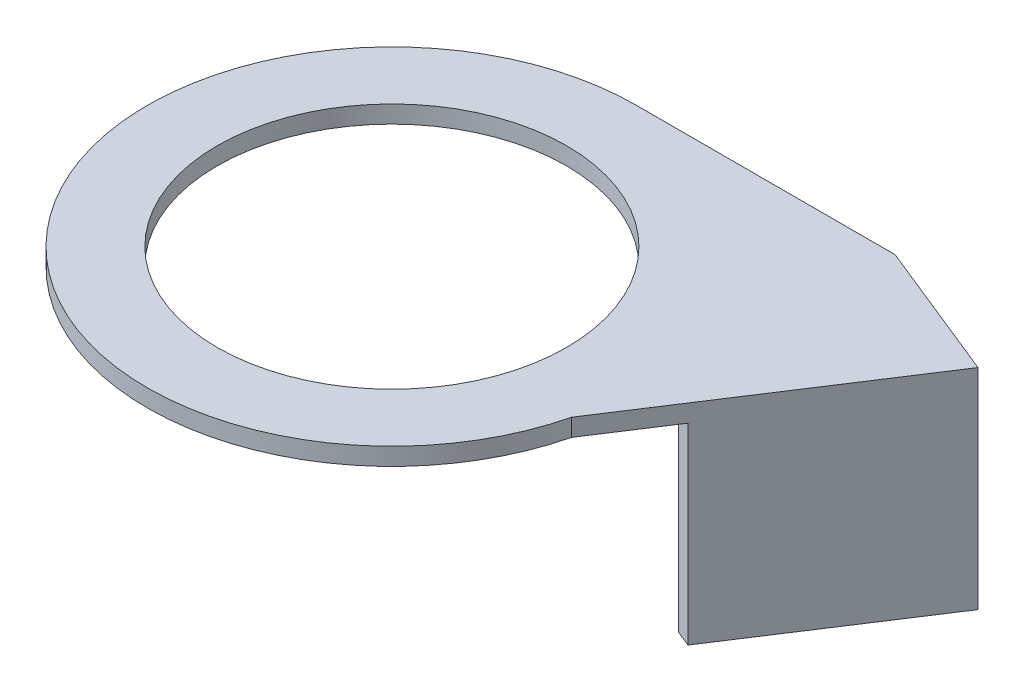
SolidWorks part; units mm, degrees
material "ABS"
ref_plane "Front" through (0, 0, 0) normal (0, 0, 1) x (1, 0, 0)
ref_plane "Top" through (0, 0, 0) normal (0, 1, 0) x (1, 0, 0)
ref_plane "Right" through (0, 0, 0) normal (1, 0, 0) x (0, 0, -1)
sketch "Sketch1" plane through (0, 0, 0) normal (0, 1, 0) x (1, 0, 0)
  line L0 (0, 14) -> (14.8054, 14)
  line L1 (14.8054, 14) -> (22.7702, 10.7781)
  line L2 (22.7702, 10.7781) -> (13.6017, -3.3156)
  circle A0 centre (0, 0) radius 14
  dimension "D1" = 0
extrude "Boss-Extrude1" add sketch "Sketch1" along normal blind 1 contours A0 | A0 L2 L1 L0
sketch "Sketch2" plane through (0, 0, 0) normal (0, -1, 0) x (-1, 0, 0)
  line L0 (-22.7702, 10.7781) -> (-21.8432, 11.1531)
  line L1 (-14.8054, 14) -> (-22.7702, 10.7781) construction
  line L2 (-21.8432, 11.1531) -> (-15.2995, 1.0942)
  line L3 (-22.7702, 10.7781) -> (-13.6017, -3.3156) construction
  line L4 (-22.7702, 10.7781) -> (-16.2265, 0.7192)
  line L5 (-16.2265, 0.7192) -> (-15.2995, 1.0942)
  dimension "D1" = 12
extrude "Boss-Extrude2" add sketch "Sketch2" along normal blind 11
sketch "Sketch3" plane through (0, 0, 0) normal (0, -1, 0) x (-1, 0, 0)
  line L0 (-18.0654, 12.6812) -> (-14.3982, 7.044)
  line L3 (-14.8054, 14) -> (-21.8432, 11.1531) construction
  line L5 (-18.0654, 12.6812) -> (-14.8054, 14)
  line L6 (-14.8054, 14) -> (-7.8054, 14)
  line L7 (0, 14) -> (-14.8054, 14) construction
  arc A0 (-7.8054, 14) -> (-14.3982, 7.044) centre (0, 0) ccw
extrude "Boss-Extrude3" add sketch "Sketch3" along normal blind 11
sketch "Sketch4" plane through (0, 0, 0) normal (0, -1, 0) x (1, 0, 0)
  circle A0 centre (0, 0) radius 10
extrude "Cut-Extrude1" cut sketch "Sketch4" against normal blind 11
